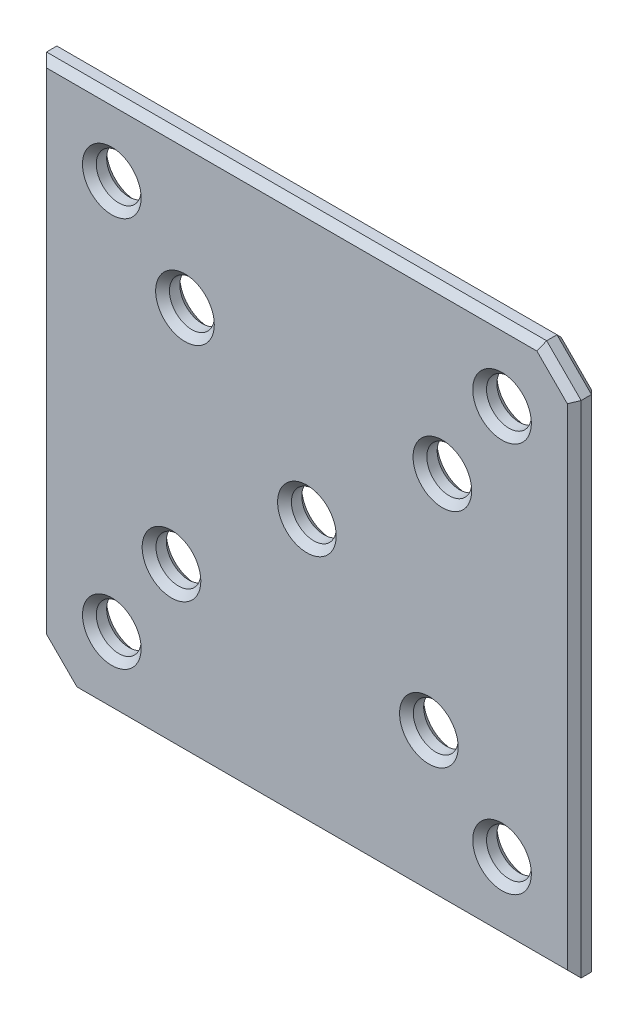
SolidWorks part; units mm, degrees
ref_plane "前视" through (0, 0, 0) normal (0, 0, 1) x (1, 0, 0)
ref_plane "上视" through (0, 0, 0) normal (0, 1, 0) x (1, 0, 0)
ref_plane "右视" through (0, 0, 0) normal (1, 0, 0) x (0, 0, -1)
sketch "草图1" plane through (0, 0, 0) normal (0, 0, 1) x (1, 0, 0)
  line L0 (-1611.3839, 0) -> (1936.635, 0) construction
  line L1 (135, 155) -> (155, 135)
  line L2 (0, 1418.2496) -> (0, -1054.9444) construction
  line L3 (-155, 155) -> (135, 155)
  line L4 (-155, 155) -> (-155, -135)
  line L5 (-135, -155) -> (155, -155)
  line L6 (155, 135) -> (155, -155)
  line L7 (-155, -135) -> (-135, -155)
  line L8 (-241.7498, -241.7498) -> (0, 0) construction
  line L9 (0, 0) -> (269.6196, 269.6196) construction
  line L10 (262.9093, -262.9093) -> (0, 0) construction
  line L11 (0, 0) -> (-278.609, 278.609) construction
  line L12 (0, 0) -> (-785, -619) construction
  line L13 (0, 0) -> (-50.8921, -40.1302) construction
  line L14 (0, 0) -> (171.8618, 135.5191) construction
  circle A0 centre (-113.1371, -113.1371) radius 13
  circle A1 centre (-78.5241, -61.919) radius 13
  circle A2 centre (78.5241, 61.919) radius 13
  circle A3 centre (113.1371, 113.1371) radius 13
  circle A4 centre (-70.7107, 70.7107) radius 13
  circle A5 centre (-113.1371, 113.1371) radius 13
  circle A6 centre (70.7107, -70.7107) radius 13
  circle A7 centre (113.1371, -113.1371) radius 13
  circle A8 centre (0, 0) radius 13
  dimension "D9" = 160
  dimension "D7" = 45
  dimension "D17" = 26
  dimension "D18" = 26
  dimension "D1" = 310
  dimension "D2" = 310
  dimension "D3" = 20
  dimension "D4" = 20
  dimension "D5" = 20
  dimension "D6" = 20
  dimension "D8" = 45
  dimension "D10" = 619
  dimension "D11" = 785
  dimension "D12" = 100
  dimension "D13" = 100
  dimension "D14" = 160
  dimension "D15" = 100
  dimension "D16" = 60
extrude "基体-拉伸" add sketch "草图1" along normal blind 14
chamfer "倒角1" distance 4 angle 45 30 edges at (100.1371, -113.1371, 0) (57.7107, -70.7107, 0) (-57.7107, 70.7107, 0) (91.5241, 61.919, 0) (-100.1371, -113.1371, 0) (-145, -145, 0) (10, -155, 0) (155, -10, 0) (145, 145, 0) (-10, 155, 0) (-155, 10, 0) (-65.5241, -61.919, 0) (126.1371, 113.1371, 0) (-100.1371, 113.1371, 0) (13, 0, 0) (100.1371, -113.1371, 14) (57.7107, -70.7107, 14) (-57.7107, 70.7107, 14) (91.5241, 61.919, 14) (-100.1371, -113.1371, 14) (-10, 155, 14) (145, 145, 14) (155, -10, 14) (10, -155, 14) (-145, -145, 14) (-155, 10, 14) (-65.5241, -61.919, 14) (126.1371, 113.1371, 14) (-100.1371, 113.1371, 14) (13, 0, 14)
